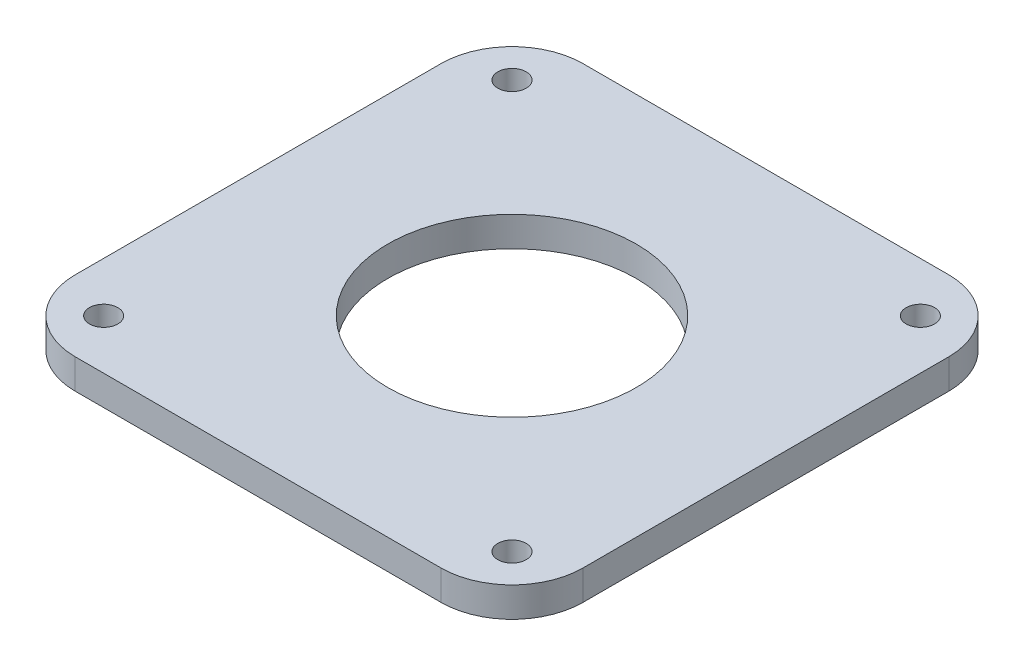
SolidWorks part; units mm, degrees
ref_plane "Front Plane" through (0, 0, 0) normal (0, 0, 1) x (1, 0, 0)
ref_plane "Top Plane" through (0, 0, 0) normal (0, 1, 0) x (1, 0, 0)
ref_plane "Right Plane" through (0, 0, 0) normal (1, 0, 0) x (0, 0, -1)
sketch "Sketch1" plane through (0, 0, 0) normal (0, 1, 0) x (1, 0, 0)
  line L1 (-35.75, 35.75) -> (35.75, 35.75)
  line L2 (-35.75, 35.75) -> (-35.75, -35.75)
  line L3 (-35.75, -35.75) -> (35.75, -35.75)
  line L4 (35.75, 35.75) -> (35.75, -35.75)
  line L5 (-35.75, 35.75) -> (35.75, -35.75) construction
  line L6 (-35.75, -35.75) -> (35.75, 35.75) construction
  point P0 (0, 0)
  dimension "D1" = 71.5
  dimension "D2" = 71.5
extrude "Boss-Extrude1" add sketch "Sketch1" along normal blind 4.2
fillet "Fillet1" radius 10 4 edges at (35.75, 2.1, -35.75) (-35.75, 2.1, -35.75) (-35.75, 2.1, 35.75) (35.75, 2.1, 35.75)
sketch "Sketch2" plane through (0, 4.2, 0) normal (0, 1, 0) x (1, 0, 0)
  circle A0 centre (0, 0) radius 17.5
  dimension "D1" = 35
extrude "Cut-Extrude1" cut sketch "Sketch2" against normal through all
sketch "Sketch3" plane through (0, 4.2, 0) normal (0, 1, 0) x (1, 0, 0)
  line L0 (25.75, 35.75) -> (-25.75, 35.75) construction
  line L1 (-35.75, 25.75) -> (-35.75, -25.75) construction
  line L2 (-28.75, 28.75) -> (-69.288, 28.75) construction
  line L3 (-28.75, 28.75) -> (-28.75, -40.2196) construction
  line L4 (35.75, -25.75) -> (35.75, 25.75) construction
  line L5 (-25.75, -35.75) -> (25.75, -35.75) construction
  line L6 (-28.75, -28.75) -> (60.1312, -28.75) construction
  line L7 (28.75, 28.75) -> (28.75, 43.7018) construction
  circle A0 centre (-28.75, 28.75) radius 2
  circle A1 centre (28.75, 28.75) radius 2
  circle A2 centre (-28.75, -28.75) radius 2
  circle A3 centre (28.75, -28.75) radius 2
  dimension "D1" = 4
  dimension "D2" = 4
  dimension "D3" = 4
  dimension "D4" = 4
  dimension "D5" = 7
  dimension "D6" = 7
  dimension "D7" = 7
  dimension "D8" = 7
extrude "Cut-Extrude2" cut sketch "Sketch3" against normal through all
